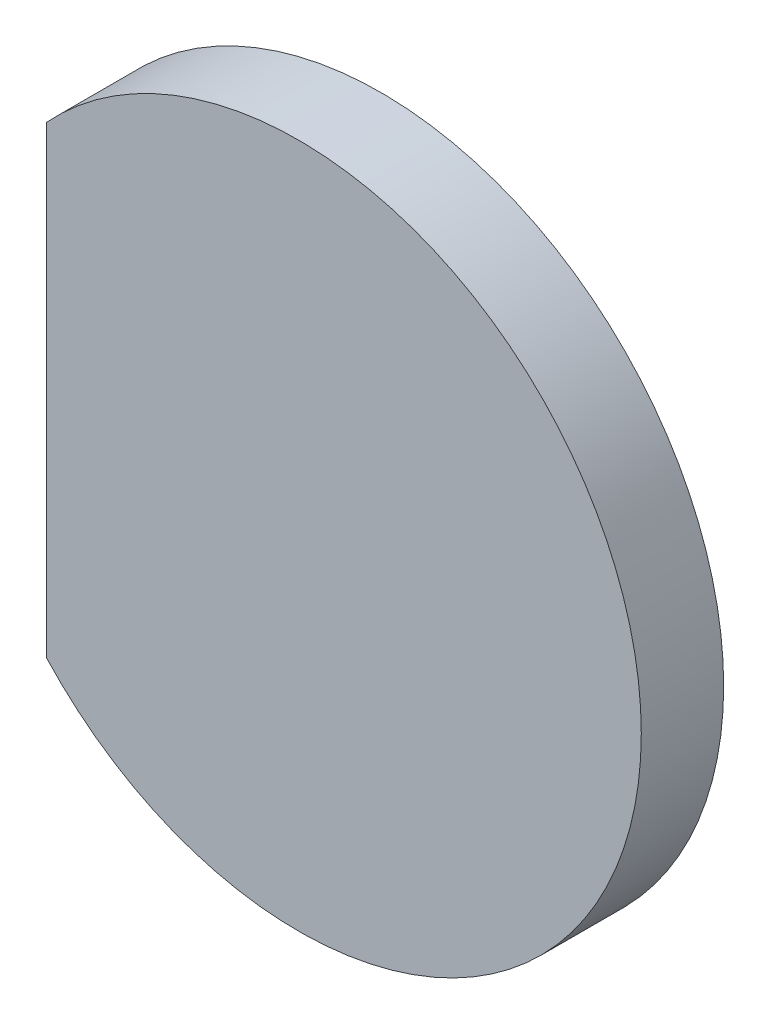
SolidWorks part; units mm, degrees
material "POLYURETHANE (11671)"
ref_plane "Front Plane" through (0, 0, 0) normal (0, 0, 1) x (1, 0, 0)
ref_plane "Top Plane" through (0, 0, 0) normal (0, 1, 0) x (1, 0, 0)
ref_plane "Right Plane" through (0, 0, 0) normal (1, 0, 0) x (0, 0, -1)
sketch "Sketch1" plane through (0, 0, 0) normal (0, 0, 1) x (1, 0, 0)
  line L3 (-42.9355, 39.4175) -> (-42.9355, -39.4175)
  arc A2 (-42.9355, 39.4175) -> (-42.9355, -39.4175) centre (0, 0) cw
  point P3 (0, 0)
  point P4 (-42.9355, 0)
  point P5 (58.2855, 0)
  dimension "D2" = 101.221
  dimension "D1" = 78.835
extrude "Boss-Extrude1" add sketch "Sketch1" along normal blind 14.017
equation "\"width\"=0.101221"
equation "\"height\"=0.078835"
equation "\"stop_width\"=0.005000"
equation "\"t1\"=0.005000"
equation "\"t2\"=0.029258"
equation "\"t3\"=0.009379"
equation "\"D2@Sketch1\"=\"width\"*1000"
equation "\"bolt_hole_size\"=0.003000"
equation "\"b1_x\"=0.045823"
equation "\"b1_y\"=0.029076"
equation "\"bolt_dist\"=0.042000"
equation "\"bolt_hole_depth\"=0.005000"
equation "\"D1\"= \"bolt_hole_depth\" * 1000"
equation "\"pitch\"=0.000500"
equation "\"cover_holes_diam\"=0.002000"
equation "\"cover_holes_depth\"=0.004000"
equation "\"cover_hole_pitch\"=0.000400"
equation "\"D1@Sketch1\"=\"height\"*1000"
equation "\"inf_stop_x\"=0.027955"
equation "\"superior_stop_x\"=0.021901"
equation "\"superior_stop_angle\"=107.704683"
equation "\"theta_p_init\"=73.816587"
equation "\"D1@Boss-Extrude1\"=\"pad_t\"*1000"
equation "\"pad_t\"=0.014017"
